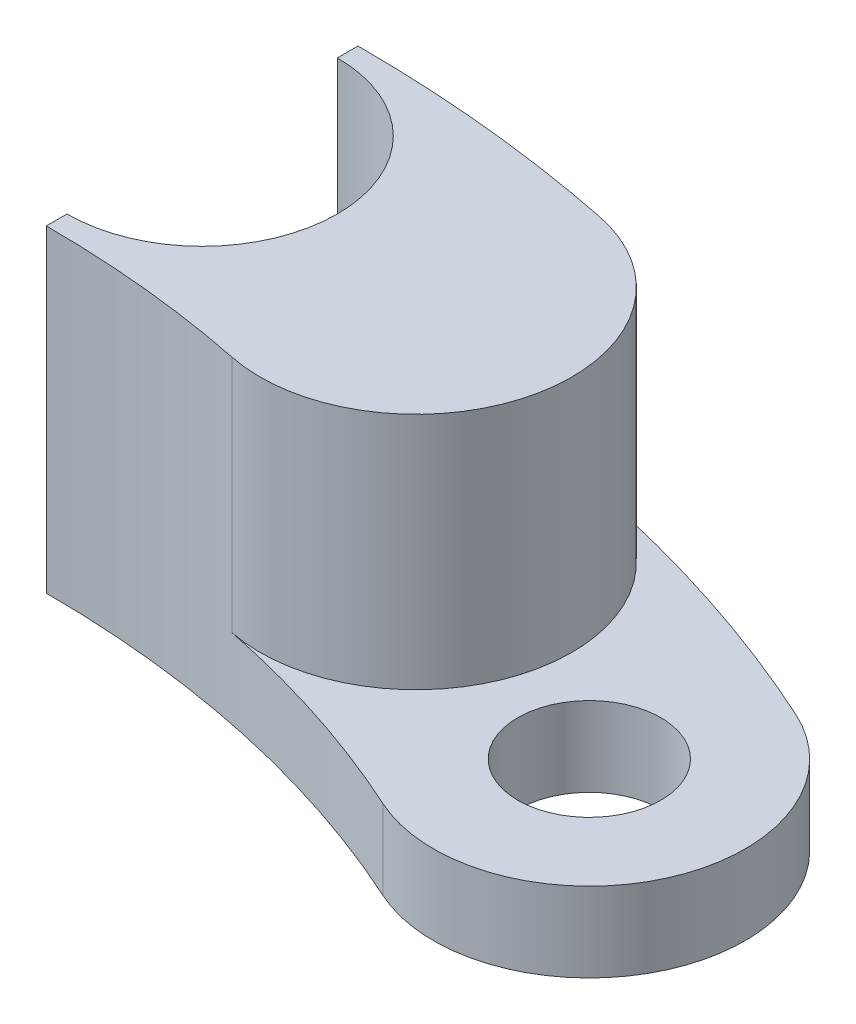
SolidWorks part; units mm, degrees
material "ﾎﾟﾘｴｽﾃﾙ樹脂"
ref_plane "正面" through (0, 0, 0) normal (0, 0, 1) x (1, 0, 0)
ref_plane "平面" through (0, 0, 0) normal (0, 1, 0) x (1, 0, 0)
ref_plane "右側面" through (0, 0, 0) normal (1, 0, 0) x (0, 0, -1)
sketch "ｽｹｯﾁ1" plane through (0, 0, 0) normal (0, 1, 0) x (1, 0, 0)
  line L0 (0, 0) -> (0, 42.4)
  line L1 (0, 0) -> (8.4532, 41.5488)
  line L2 (0, 0) -> (17.583, 38.5824) construction
  circle A0 centre (0, 0) radius 32.4 construction
  circle A1 centre (0, 0) radius 42.6 construction
  circle A2 centre (0, 0) radius 42.4
  circle A3 centre (0, 0) radius 32.6
  circle A4 centre (15.551, 34.1235) radius 2.25
  circle A5 centre (0, 0) radius 37.5 construction
  circle A6 centre (0, 37.5) radius 4.25
  circle A7 centre (15.551, 34.1235) radius 4.9
  circle A8 centre (-15.551, 34.1235) radius 2.25
  circle A9 centre (-15.551, 34.1235) radius 4.9
  dimension "D1" = 85.2
  dimension "D2" = 64.8
  dimension "D3" = 84.8
  dimension "D4" = 65.2
  dimension "D6" = 4.5
  dimension "D8" = 75
  dimension "D9" = 8.5
  dimension "D5" = 11.5
  dimension "D7" = 13
extrude "ﾎﾞｽ - 押し出し1" add sketch "ｽｹｯﾁ1" along normal blind 10 contours A7 A2 L1 A3 | A7 A4 | A6 L0 A3 L1 A2
sketch "ｽｹｯﾁ2" plane through (0, 10, 0) normal (0, 1, 0) x (1, 0, 0)
  line L0 (0, 0) -> (8.4532, 41.5488) construction
  line L1 (0, 0) -> (0, 50000) construction
  circle A1 centre (7.4763, 36.7472) radius 4.9
  circle A3 centre (15.551, 34.1235) radius 4.9
  circle A4 centre (0, 0) radius 32.6
  circle A5 centre (0, 0) radius 42.4
  circle A6 centre (-7.4763, 36.7472) radius 4.9
  circle A7 centre (-15.551, 34.1235) radius 4.9
  arc M5 (0, 32.6) -> (13.519, 29.6647) centre (0, 0) cw
  arc M6 (13.519, 29.6647) -> (17.583, 38.5824) centre (15.551, 34.1235) ccw
  arc M7 (17.583, 38.5824) -> (0, 42.4) centre (0, 0) ccw
  circle M9 centre (15.551, 34.1235) radius 2.25
  dimension "D2" = 9.8
  dimension "D3" = 84.8
  dimension "D4" = 65.2
  dimension "D1" = 11.5
extrude "ｶｯﾄ - 押し出し1" cut sketch "ｽｹｯﾁ2" against normal blind 7.5 contours A3 A1 M7 | A3 A1 M6 M9 | A3 A1 M5 | A5
